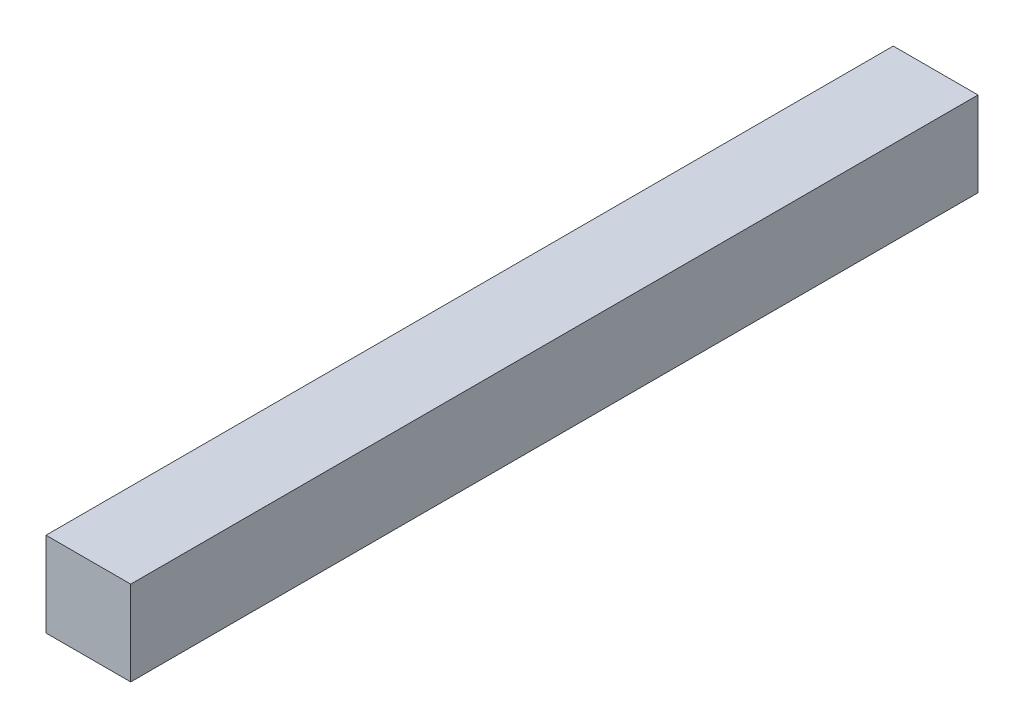
SolidWorks part; units mm, degrees
ref_plane "Přední rovina" through (0, 0, 0) normal (0, 0, 1) x (1, 0, 0)
ref_plane "Horní rovina" through (0, 0, 0) normal (0, 1, 0) x (1, 0, 0)
ref_plane "Pravá rovina" through (0, 0, 0) normal (1, 0, 0) x (0, 0, -1)
sketch "Sketch1" plane through (0, 0, 0) normal (0, 0, 1) x (1, 0, 0)
  line L1 (0, 0) -> (10, 0)
  line L2 (0, 0) -> (0, 10)
  line L3 (0, 10) -> (10, 10)
  line L4 (10, 0) -> (10, 10)
  dimension "D1" = 10
  dimension "D2" = 10
extrude "Boss-Extrude1" add sketch "Sketch1" along normal blind 100
